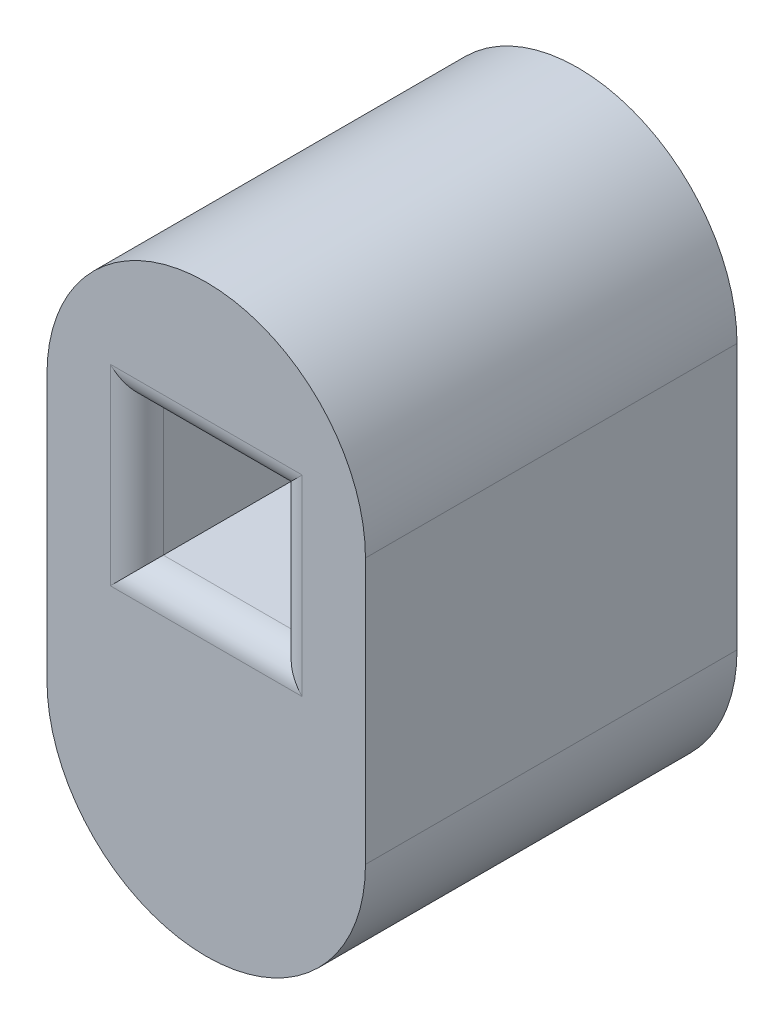
SolidWorks part; units mm, degrees
ref_plane "Front Plane" through (0, 0, 0) normal (0, 0, 1) x (1, 0, 0)
ref_plane "Top Plane" through (0, 0, 0) normal (0, 1, 0) x (1, 0, 0)
ref_plane "Right Plane" through (0, 0, 0) normal (1, 0, 0) x (0, 0, -1)
sketch "Sketch1" plane through (0, 0, 0) normal (0, 0, 1) x (1, 0, 0)
  line L0 (0, 0) -> (0, 10) construction
  line L1 (-6, 0) -> (-6, 10)
  line L2 (6, 0) -> (6, 10)
  line L4 (-2.615, 5.285) -> (2.615, 5.285)
  line L5 (-2.615, 5.285) -> (-2.615, 10.515)
  line L6 (-2.615, 10.515) -> (2.615, 10.515)
  line L7 (2.615, 5.285) -> (2.615, 10.515)
  line L8 (-2.615, 5.285) -> (2.615, 10.515) construction
  line L9 (-2.615, 10.515) -> (2.615, 5.285) construction
  arc A0 (-6, 0) -> (6, 0) centre (0, 0) ccw
  arc A1 (6, 10) -> (-6, 10) centre (0, 10) ccw
  point P3 (0, 5)
  point P8 (0, 7.9)
  dimension "D2" = 6
  dimension "D1" = 10
  dimension "D3" = 5.23
  dimension "D4" = 7.9
extrude "Boss-Extrude1" add sketch "Sketch1" along normal blind 14
fillet "Fillet1" radius 1 4 edges at (0, 5.285, 14) (-2.615, 7.9, 14) (0, 10.515, 14) (2.615, 7.9, 14)
fillet "Fillet2" radius 1 4 edges at (-2.615, 7.9, 0) (0, 5.285, 0) (2.615, 7.9, 0) (0, 10.515, 0)
